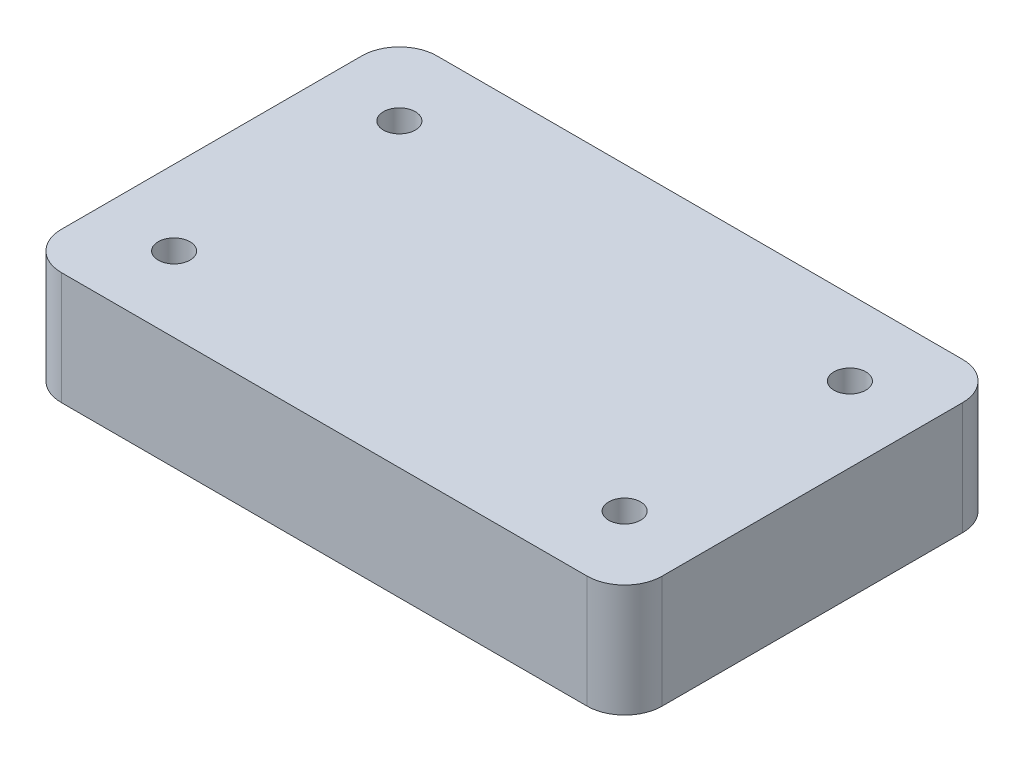
SolidWorks part; units mm, degrees
ref_plane "Alzado" through (0, 0, 0) normal (0, 0, 1) x (1, 0, 0)
ref_plane "Planta" through (0, 0, 0) normal (0, 1, 0) x (1, 0, 0)
ref_plane "Vista lateral" through (0, 0, 0) normal (1, 0, 0) x (0, 0, -1)
sketch "Croquis1" plane through (0, 0, 0) normal (0, 1, 0) x (1, 0, 0)
  line L1 (-70, -50) -> (70, -50)
  line L2 (-80, -40) -> (-80, 40)
  line L3 (-70, 50) -> (70, 50)
  line L4 (80, -40) -> (80, 40)
  line L5 (-80, -50) -> (80, 50) construction
  line L6 (-80, 50) -> (80, -50) construction
  arc A0 (-80, 40) -> (-70, 50) centre (-70, 40) cw
  arc A1 (-70, -50) -> (-80, -40) centre (-70, -40) cw
  arc A2 (70, -50) -> (80, -40) centre (70, -40) ccw
  arc A3 (70, 50) -> (80, 40) centre (70, 40) cw
  point P0 (0, 0)
  dimension "D3" = 10
  dimension "D1" = 100
  dimension "D2" = 160
extrude "Saliente-Extruir1" add sketch "Croquis1" along normal blind 30
hole_wizard "Taladro roscado M10x1.51" positions "Croquis3" profile "Croquis4" tap size "M10x1.5" standard "Ansi Metric" end condition through all
sketch "Croquis3" plane through (0, 30, 0) normal (0, 1, 0) x (1, 0, 0)
  line L0 (0, 50) -> (0, 0) construction
  line L1 (70, 50) -> (-70, 50) construction
  line L2 (0, 0) -> (80, 0) construction
  line L3 (80, -40) -> (80, 40) construction
  point P0 (-60, 30)
  point P2 (60, 30)
  point P4 (60, -30)
  point P6 (-60, -30)
  dimension "D1" = 60
  dimension "D2" = 60
  dimension "D3" = 30
  dimension "D4" = 30
  dimension "D5" = 30
  dimension "D6" = 30
  dimension "D7" = 60
  dimension "D8" = 60
sketch "Croquis4" plane through (-60, 30, -30) normal (1, 0, 0) x (0, 0, 1)
  line L0 (0, 0) -> (0, 30)
  line L1 (0, 30) -> (4.25, 30)
  line L2 (4.25, 30) -> (4.25, 0)
  line L5 (4.25, 0) -> (0, 0)
  line L11 (0, -6.35) -> (0, 107.95) construction
  dimension "Diámetro de perforador para roscar hasta el siguiente" = 8.5
  dimension "Profundidad de perforador para roscar hasta el siguiente" = 30
cosmetic thread "Rosca de taladro1" parameters "D2"=10
cosmetic thread "Rosca de taladro2" parameters "D2"=10
cosmetic thread "Rosca de taladro3" parameters "D2"=10
cosmetic thread "Rosca de taladro4" parameters "D2"=10
